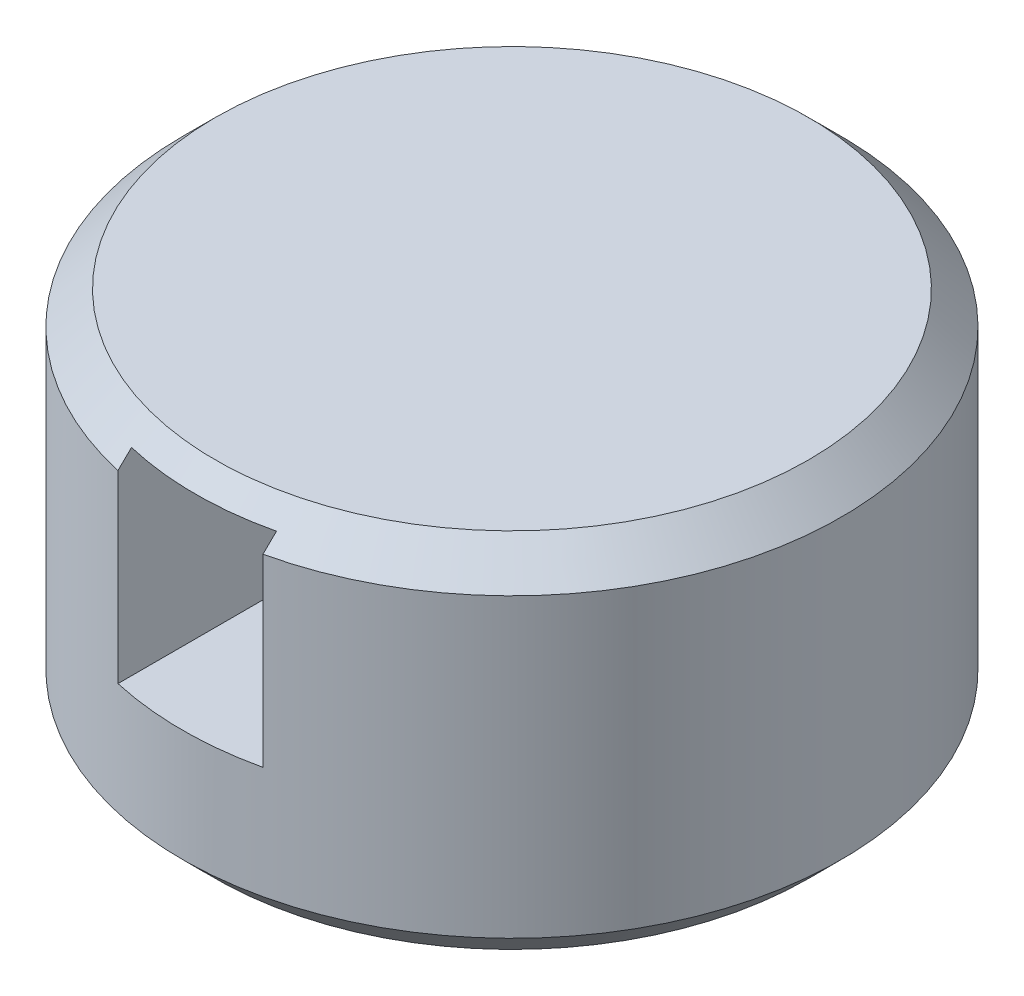
SolidWorks part; units mm, degrees
ref_plane "Front Plane" through (0, 0, 0) normal (0, 0, 1) x (1, 0, 0)
ref_plane "Top Plane" through (0, 0, 0) normal (0, 1, 0) x (1, 0, 0)
ref_plane "Right Plane" through (0, 0, 0) normal (1, 0, 0) x (0, 0, -1)
sketch "Sketch1" plane through (0, 0, 0) normal (0, 0, 1) x (1, 0, 0)
  line L0 (0, 0) -> (45, 0)
  line L1 (45, 0) -> (50, 5)
  line L2 (50, 5) -> (50, 50)
  line L3 (50, 50) -> (45, 55)
  line L4 (45, 55) -> (0, 55)
  line L5 (0, 55) -> (0, 0)
  dimension "D2" = 55
  dimension "D3" = 5
  dimension "D1" = 45
  dimension "D4" = 45
revolve "Revolve1" add sketch "Sketch1" angle 360 about L5
sketch "Sketch2" plane through (0, 0, 0) normal (0, -1, 0) x (1, 0, 0)
  line L1 (-11, 18) -> (11, 18)
  line L2 (-11, 18) -> (-11, -38)
  line L3 (-11, -38) -> (11, -38)
  line L4 (11, 18) -> (11, -38)
  line L5 (-11, 0) -> (11, 0) construction
  line L6 (0, 0) -> (0, 45) construction
  circle A0 centre (0, 0) radius 45 construction
  point P9 (0, 0)
  dimension "D1" = 22
  dimension "D2" = 56
  dimension "D3" = 18
extrude "Cut-Extrude1" cut sketch "Sketch2" against normal blind 16
sketch "Sketch3" plane through (0, 16, 0) normal (0, -1, 0) x (1, 0, 0)
  line L0 (11, -38) -> (11, 18) construction
  line L1 (11, 11.5) -> (-11, 11.5)
  line L2 (11, 11.5) -> (11, -31.5)
  line L3 (11, -31.5) -> (-11, -31.5)
  line L4 (-11, 11.5) -> (-11, -31.5)
  line L5 (-11, 18) -> (-11, -38) construction
  line L6 (-11, -38) -> (11, -38) construction
  line L7 (0, -31.5) -> (0, -38) construction
  line L8 (-11, -38) -> (11, -38) construction
  line L9 (0, 11.5) -> (0, 18) construction
  line L10 (11, 18) -> (-11, 18) construction
  dimension "D1" = 6.5
extrude "Cut-Extrude2" cut sketch "Sketch3" against normal blind 36
sketch "Sketch5" plane through (0, 0, 0) normal (0, 1, 0) x (1, 0, 0)
  circle A0 centre (0, 0) radius 12.5
  dimension "D1" = 25
extrude "Cut-Extrude4" cut sketch "Sketch5" along normal up to surface (16 mm away) up to face at (0, 16, 14.75)
sketch "Sketch6" plane through (0, 0, 11.5) normal (0, 0, -1) x (-1, 0, 0)
  line L0 (-11, 52) -> (-11, 16) construction
  line L1 (11, 52) -> (-11, 52)
  line L2 (11, 52) -> (11, 22)
  line L3 (11, 22) -> (-11, 22)
  line L4 (-11, 52) -> (-11, 22)
  dimension "D1" = 30
extrude "Cut-Extrude5" cut sketch "Sketch6" against normal through all
sketch "Sketch4" plane through (0, 16, 0) normal (0, -1, 0) x (1, 0, 0)
  line L0 (0, 18) -> (0, -38) construction
  line L1 (11, 18) -> (-11, 18) construction
  line L2 (-11, -38) -> (11, -38) construction
  line L3 (-11, -10.1) -> (11, -10.1) construction
  line L12 (11, -38) -> (11, -5.9372) construction
  line L17 (-11, -5.9372) -> (-11, -38) construction
  circle A0 centre (-5, 14.65) radius 2.13
  circle A1 centre (5, 14.65) radius 2.13
  circle A2 centre (5, -34.85) radius 2.13
  circle A3 centre (-5, -34.85) radius 2.13
  dimension "D1" = 4.26
  dimension "D4" = 4.26
  dimension "D2" = 10
  dimension "D3" = 14.65
  dimension "D5" = 49.5
extrude "Cut-Extrude3" cut sketch "Sketch4" against normal blind 10
